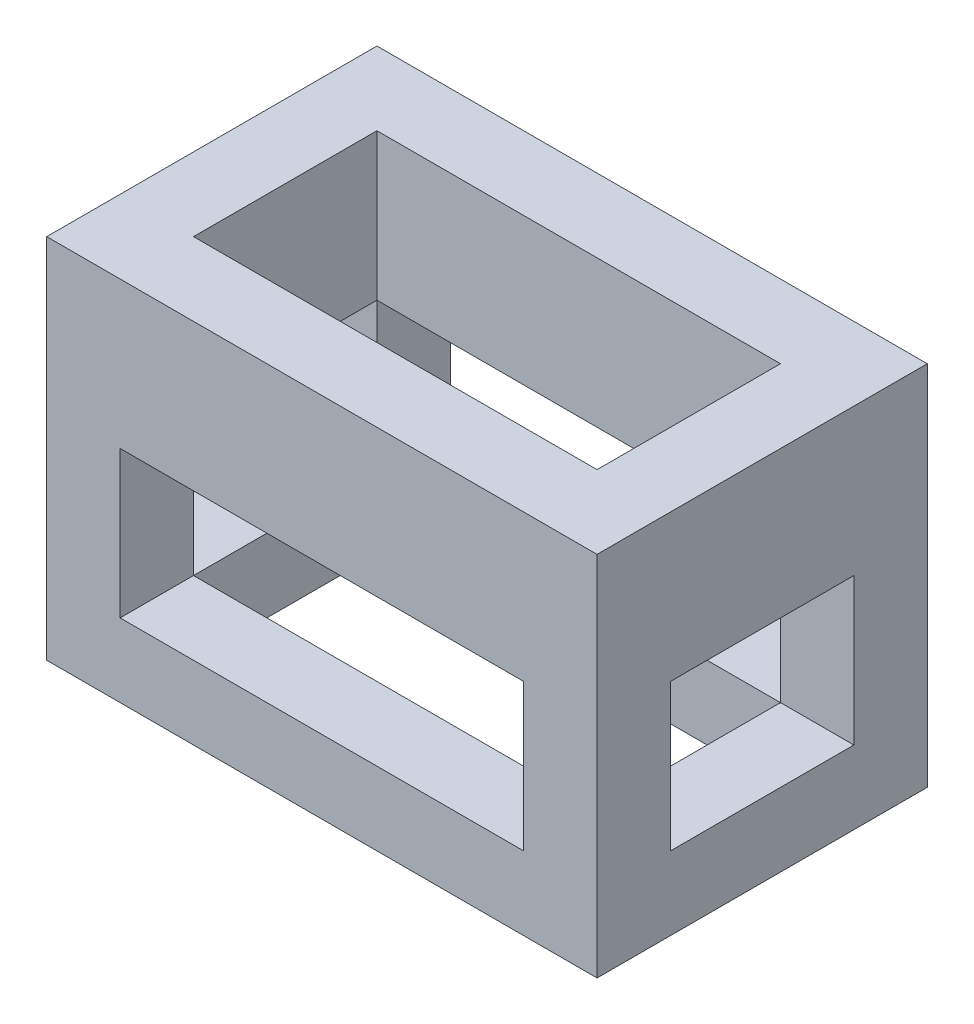
SolidWorks part; units mm, degrees
ref_plane "Front Plane" through (0, 0, 0) normal (0, 0, 1) x (1, 0, 0)
ref_plane "Top Plane" through (0, 0, 0) normal (0, 1, 0) x (1, 0, 0)
ref_plane "Right Plane" through (0, 0, 0) normal (1, 0, 0) x (0, 0, -1)
sketch "Sketch1" plane through (0, 0, 0) normal (0, 1, 0) x (1, 0, 0)
  line L1 (-95.25, -57.15) -> (95.25, -57.15)
  line L2 (-95.25, -57.15) -> (-95.25, 57.15)
  line L3 (-95.25, 57.15) -> (95.25, 57.15)
  line L4 (95.25, -57.15) -> (95.25, 57.15)
  line L5 (-95.25, -57.15) -> (95.25, 57.15) construction
  line L6 (-95.25, 57.15) -> (95.25, -57.15) construction
  point P0 (0, 0)
  dimension "D1" = 190.5
  dimension "D2" = 114.3
extrude "Boss-Extrude1" add sketch "Sketch1" along normal blind 127
sketch "Sketch2" plane through (0, 0, 57.15) normal (0, 0, 1) x (1, 0, 0)
  line L0 (-95.25, 127) -> (95.25, 127) construction
  line L1 (69.85, 25.4) -> (-69.85, 25.4)
  line L2 (69.85, 25.4) -> (69.85, 76.2)
  line L3 (69.85, 76.2) -> (-69.85, 76.2)
  line L4 (-69.85, 25.4) -> (-69.85, 76.2)
  line L5 (69.85, 25.4) -> (-69.85, 76.2) construction
  line L6 (69.85, 76.2) -> (-69.85, 25.4) construction
  line L7 (-95.25, 0) -> (95.25, 0) construction
  line L8 (-95.25, 127) -> (-95.25, 0) construction
  line L9 (95.25, 127) -> (95.25, 0) construction
  point P0 (0, 50.8)
  dimension "D1" = 50.8
  dimension "D2" = 25.4
  dimension "D3" = 25.4
  dimension "D4" = 25.4
extrude "Cut-Extrude1" cut sketch "Sketch2" against normal through all
sketch "Sketch3" plane through (95.25, 0, 0) normal (1, 0, 0) x (0, 0, -1)
  line L0 (-57.15, 127) -> (-57.15, 0) construction
  line L1 (31.75, 25.4) -> (-31.75, 25.4)
  line L2 (31.75, 25.4) -> (31.75, 76.2)
  line L3 (31.75, 76.2) -> (-31.75, 76.2)
  line L4 (-31.75, 25.4) -> (-31.75, 76.2)
  line L5 (31.75, 25.4) -> (-31.75, 76.2) construction
  line L6 (31.75, 76.2) -> (-31.75, 25.4) construction
  line L7 (57.15, 127) -> (57.15, 0) construction
  line L8 (-57.15, 127) -> (57.15, 127) construction
  line L9 (-57.15, 0) -> (57.15, 0) construction
  point P0 (0, 50.8)
  dimension "D1" = 25.4
  dimension "D2" = 25.4
  dimension "D3" = 50.8
  dimension "D4" = 25.4
extrude "Cut-Extrude2" cut sketch "Sketch3" against normal through all
sketch "Sketch4" plane through (0, 127, 0) normal (0, 1, 0) x (1, 0, 0)
  line L0 (-95.25, 57.15) -> (-95.25, -57.15) construction
  line L1 (69.85, 31.75) -> (-69.85, 31.75)
  line L2 (69.85, 31.75) -> (69.85, -31.75)
  line L3 (69.85, -31.75) -> (-69.85, -31.75)
  line L4 (-69.85, 31.75) -> (-69.85, -31.75)
  line L5 (69.85, 31.75) -> (-69.85, -31.75) construction
  line L6 (69.85, -31.75) -> (-69.85, 31.75) construction
  line L7 (95.25, 57.15) -> (-95.25, 57.15) construction
  line L8 (-95.25, -57.15) -> (95.25, -57.15) construction
  line L9 (95.25, -57.15) -> (95.25, 57.15) construction
  point P0 (0, 0)
  dimension "D1" = 25.4
  dimension "D2" = 25.4
  dimension "D3" = 25.4
  dimension "D4" = 25.4
extrude "Cut-Extrude3" cut sketch "Sketch4" against normal through all
